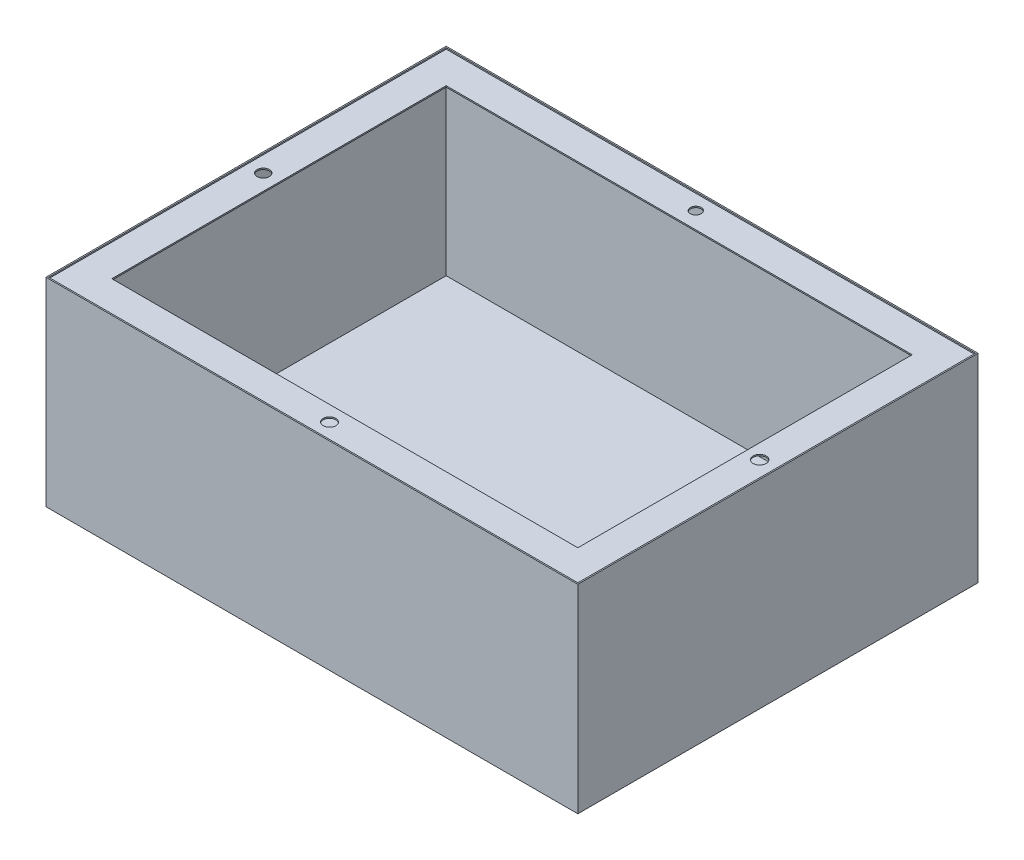
SolidWorks part; units mm, degrees
ref_plane "Front Plane" through (0, 0, 0) normal (0, 0, 1) x (1, 0, 0)
ref_plane "Top Plane" through (0, 0, 0) normal (0, 1, 0) x (1, 0, 0)
ref_plane "Right Plane" through (0, 0, 0) normal (1, 0, 0) x (0, 0, -1)
sketch "Sketch1" plane through (0, 0, 0) normal (0, 1, 0) x (1, 0, 0)
  line L1 (-205.2, 154.4) -> (205.2, 154.4)
  line L2 (-205.2, 154.4) -> (-205.2, -154.4)
  line L3 (-205.2, -154.4) -> (205.2, -154.4)
  line L4 (205.2, 154.4) -> (205.2, -154.4)
  line L5 (-205.2, 154.4) -> (205.2, -154.4) construction
  line L6 (-205.2, -154.4) -> (205.2, 154.4) construction
  point P0 (0, 0)
  dimension "D1" = 410.4
  dimension "D2" = 308.8
extrude "Boss-Extrude2" add sketch "Sketch1" along normal blind 1
sketch "Sketch5" plane through (0, 1, 0) normal (0, 1, 0) x (1, 0, 0)
  line L1 (-205.2, 154.4) -> (-205.2, -154.4) construction
  line L2 (205.2, -154.4) -> (205.2, 154.4) construction
  line L3 (204.2, 154.4) -> (204.2, -154.4) construction
  line L4 (205.2, 154.4) -> (-205.2, 154.4) construction
  line L5 (-205.2, -154.4) -> (205.2, -154.4) construction
  line L6 (-205.2, -153.4) -> (205.2, -153.4)
  line L10 (205.2, -154.4) -> (205.2, 154.4)
  line L11 (205.2, 154.4) -> (-205.2, 154.4)
  line L12 (-205.2, 154.4) -> (-205.2, -154.4)
  line L13 (-205.2, -154.4) -> (205.2, -154.4)
  line L14 (205.2, -154.4) -> (205.2, -153.4)
  line L16 (-205.2, -153.4) -> (-205.2, -154.4)
  line L17 (-205.2, -154.4) -> (205.2, -154.4)
  dimension "D1" = 0
  dimension "D2" = 1
  dimension "D3" = 1
extrude "Boss-Extrude4" add sketch "Sketch5" along normal blind 152.4
sketch "Sketch10" plane through (0, 1, 0) normal (0, 1, 0) x (1, 0, 0)
  line L0 (-204.2, 154.4) -> (-204.2, -154.4)
  line L1 (205.2, 154.4) -> (-205.2, 154.4) construction
  line L2 (-205.2, -154.4) -> (205.2, -154.4) construction
  line L3 (-205.2, 154.4) -> (-205.2, -153.4) construction
  dimension "D1" = 1
extrude "Extrude-Thin2" add sketch "Sketch10" along normal blind 152.4 thin
sketch "Sketch11" plane through (0, 1, 0) normal (0, 1, 0) x (1, 0, 0)
  line L0 (204.2, 154.4) -> (204.2, -153.4)
  line L1 (205.2, 154.4) -> (-204.2, 154.4) construction
  line L2 (205.2, -153.4) -> (-204.2, -153.4) construction
  line L3 (-204.2, 153.4) -> (205.2, 153.4)
  line L4 (-204.2, 154.4) -> (-204.2, -153.4) construction
  line L5 (205.2, -153.4) -> (205.2, 154.4) construction
  dimension "D1" = 1
  dimension "D2" = 1
extrude "Extrude-Thin3" add sketch "Sketch11" along normal blind 152.4 thin thin type one direction reverse wall 1
sketch "Sketch12" plane through (0, 0, -154.4) normal (0, 0, -1) x (-1, 0, 0)
  line L0 (-205.2, 152.4) -> (205.2, 152.4)
  line L1 (-205.2, 153.4) -> (-205.2, 0) construction
  line L2 (205.2, 153.4) -> (205.2, 0) construction
  line L3 (205.2, 153.4) -> (-205.2, 153.4) construction
  dimension "D1" = 1
extrude "Extrude-Thin4" add sketch "Sketch12" against normal blind 25.4 thin
sketch "Sketch13" plane through (-205.2, 0, 0) normal (-1, 0, 0) x (0, 0, 1)
  line L0 (-154.4, 152.4) -> (154.4, 152.4)
  line L1 (-154.4, 153.4) -> (-154.4, 0) construction
  line L2 (154.4, 153.4) -> (154.4, 0) construction
  line L3 (-154.4, 153.4) -> (154.4, 153.4) construction
  dimension "D1" = 1
extrude "Extrude-Thin5" add sketch "Sketch13" against normal blind 25.4 thin
sketch "Sketch14" plane through (0, 0, 154.4) normal (0, 0, 1) x (1, 0, 0)
  line L0 (-205.2, 152.4) -> (205.2, 152.4)
  line L1 (-205.2, 153.4) -> (-205.2, 0) construction
  line L2 (205.2, 153.4) -> (205.2, 0) construction
  line L3 (-205.2, 153.4) -> (205.2, 153.4) construction
  dimension "D1" = 1
extrude "Extrude-Thin6" add sketch "Sketch14" against normal blind 25.4 thin
sketch "Sketch15" plane through (205.2, 0, 0) normal (1, 0, 0) x (0, 0, -1)
  line L0 (-154.4, 152.4) -> (154.4, 152.4)
  line L1 (-154.4, 153.4) -> (-154.4, 0) construction
  line L2 (154.4, 153.4) -> (154.4, 0) construction
  line L3 (-154.4, 153.4) -> (154.4, 153.4) construction
  dimension "D1" = 1
extrude "Extrude-Thin7" add sketch "Sketch15" against normal blind 25.4 thin
sketch "Sketch19" plane through (0, 152.4, 0) normal (0, 1, 0) x (1, 0, 0)
  circle A0 centre (191.1045, 0) radius 5.0561
  circle A1 centre (-191.953, 0) radius 4.7371
  circle A2 centre (0, 141.8347) radius 4.1943
  circle A3 centre (0, -140.7655) radius 4.8873
extrude "Cut-Extrude3" cut sketch "Sketch19" against normal blind 10
sketch "Sketch20" plane through (0, 0, 0) normal (0, -1, 0) x (1, 0, 0)
  line L1 (-205.2, -154.4) -> (-205.2, 154.4) construction
  line L2 (205.2, 154.4) -> (205.2, -154.4) construction
  line L3 (155.2, 154.4) -> (155.2, -154.4) construction
  line L4 (-205.2, 154.4) -> (205.2, 154.4) construction
  line L5 (205.2, -154.4) -> (-205.2, -154.4) construction
  line L7 (-155.2, -154.4) -> (-155.2, 154.4) construction
  dimension "D1" = 50
  dimension "D2" = 50
